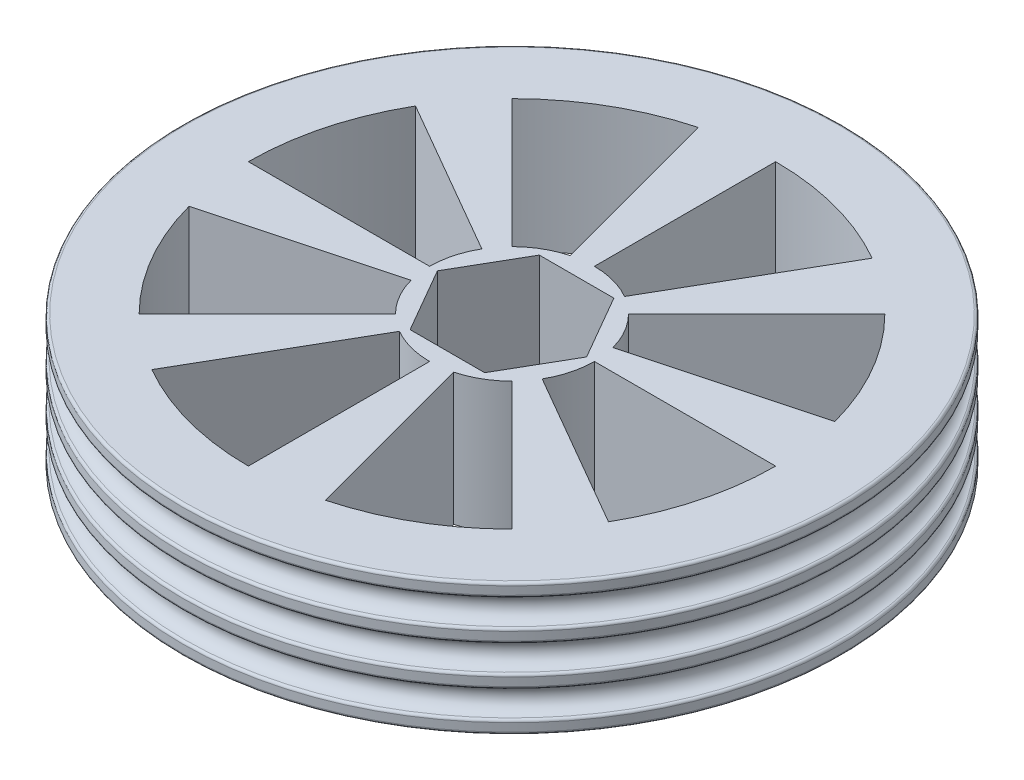
SolidWorks part; units mm, degrees
ref_plane "Front Plane" through (0, 0, 0) normal (0, 0, 1) x (1, 0, 0)
ref_plane "Top Plane" through (0, 0, 0) normal (0, 1, 0) x (1, 0, 0)
ref_plane "Right Plane" through (0, 0, 0) normal (1, 0, 0) x (0, 0, -1)
sketch "Sketch1" plane through (0, 0, 0) normal (0, 1, 0) x (1, 0, 0)
  circle A0 centre (0, 0) radius 31.75
  circle A1 centre (0, 0) radius 2.54
  dimension "D1" = 63.5
  dimension "D2" = 5.08
extrude "Boss-Extrude1" add sketch "Sketch1" along normal blind 12.7 contours A0 A1
sketch "Sketch2" plane through (0, 12.7, 0) normal (0, 1, 0) x (1, 0, 0)
  line L1 (-7.1857, 0) -> (-3.5929, -6.223)
  line L2 (-3.5929, -6.223) -> (3.5929, -6.223)
  line L3 (3.5929, -6.223) -> (7.1857, 0)
  line L4 (7.1857, 0) -> (3.5929, 6.223)
  line L5 (3.5929, 6.223) -> (-3.5929, 6.223)
  line L6 (-3.5929, 6.223) -> (-7.1857, 0)
  circle A0 centre (0, 0) radius 6.223 construction
  dimension "D1" = 12.446
extrude "Cut-Extrude1" cut sketch "Sketch2" against normal blind 9.525
sketch "Sketch3" plane through (0, 0, 0) normal (0, -1, 0) x (1, 0, 0)
  line L0 (0, 0) -> (0, -25.4)
  line L1 (0, 0) -> (12.7, -21.997)
  circle A0 centre (0, 0) radius 25.4
  circle A1 centre (0, 0) radius 7.9375
  dimension "D1" = 15.875
  dimension "D2" = 50.8
  dimension "D3" = 30
extrude "Cut-Extrude2" cut sketch "Sketch3" against normal through all contours A1 L0 A0 L1
pattern_circular "CirPattern1" count 8 over 360 about axis through (0, 0, 0) along (0, 1, 0) of "Cut-Extrude2"
sketch "Sketch4" plane through (0, 0, 0) normal (0, 0, 1) x (1, 0, 0)
  line L0 (0, 0) -> (-31.75, 0)
  line L1 (-31.75, 0) -> (-31.75, 12.7)
  line L3 (0, 0) -> (0, 12.7)
  circle A0 centre (-31.75, 2.54) radius 1.27
  circle A1 centre (-31.75, 10.16) radius 1.27
  circle A2 centre (-31.75, 6.35) radius 1.27
  dimension "D1" = 2.54
  dimension "D2" = 2.54
  dimension "D3" = 2.54
  dimension "D4" = 6.35
  dimension "D5" = 2.54
  dimension "D6" = 2.54
revolve "Cut-Revolve1" cut sketch "Sketch4" angle 360 about L3
fillet "Fillet1" radius 0.254 8 edges at (0, 12.7, 31.75) (0, 11.43, -31.75) (0, 8.89, 31.75) (0, 7.62, -31.75) (0, 5.08, 31.75) (0, 3.81, -31.75) (0, 1.27, 31.75) (0, 0, 31.75)
